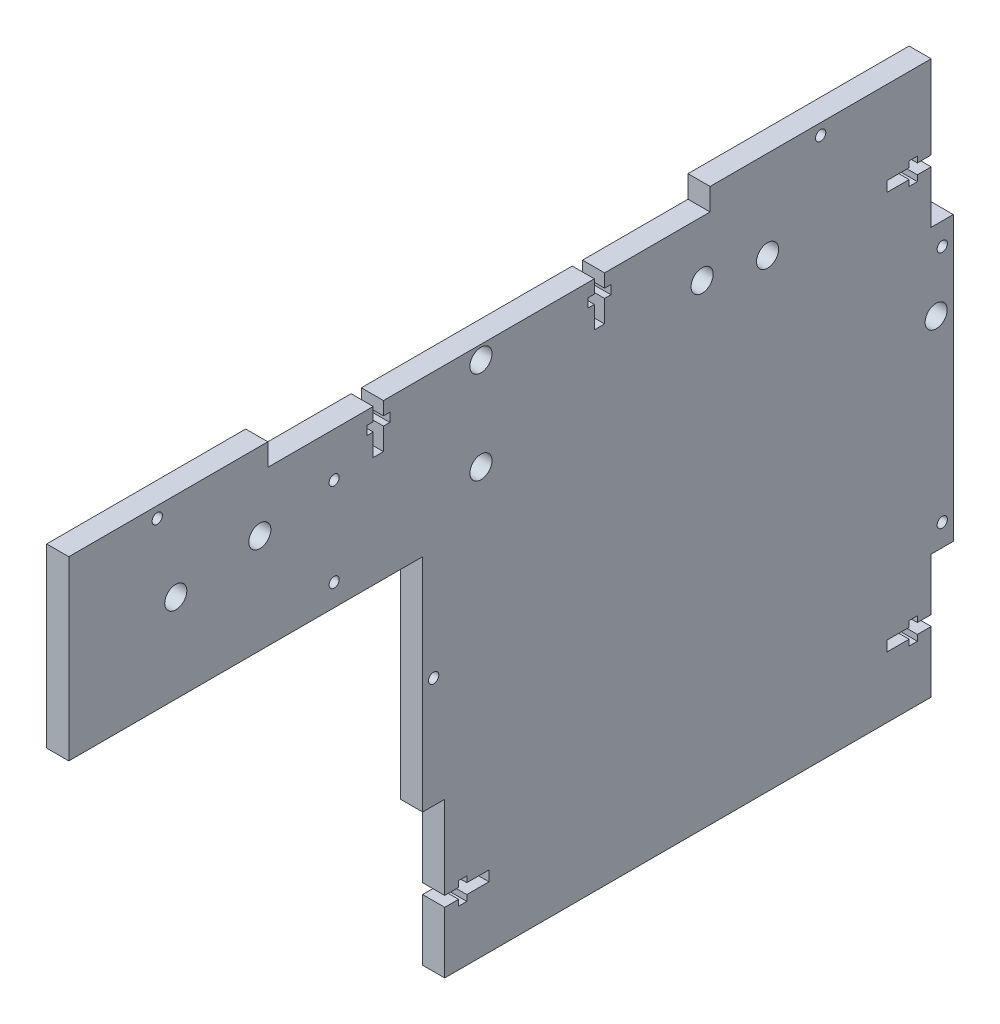
SolidWorks part; units mm, degrees
material "Acrylic (Medium-high impact)"
ref_plane "Front Plane" through (0, 0, 0) normal (0, 0, 1) x (1, 0, 0)
ref_plane "Top Plane" through (0, 0, 0) normal (0, 1, 0) x (1, 0, 0)
ref_plane "Right Plane" through (0, 0, 0) normal (1, 0, 0) x (0, 0, -1)
sketch "Sketch1" plane through (0, 0, 0) normal (1, 0, 0) x (0, 0, -1)
  line L1 (0, 0) -> (139.7, 0)
  line L2 (0, 0) -> (0, 107.95)
  line L4 (139.7, 0) -> (139.7, 158.75)
  line L7 (76.2, 158.75) -> (139.7, 158.75)
  line L8 (0, 152.4) -> (76.2, 152.4)
  line L9 (76.2, 152.4) -> (76.2, 158.75)
  line L10 (0, 152.4) -> (-50.8, 152.4)
  line L11 (-50.8, 152.4) -> (-50.8, 158.75)
  line L12 (-50.8, 158.75) -> (-107.95, 158.75)
  line L13 (-107.95, 158.75) -> (-107.95, 107.95)
  line L14 (-107.95, 107.95) -> (0, 107.95)
  dimension "D1" = 158.75
  dimension "D2" = 139.7
  dimension "D3" = 152.4
  dimension "D4" = 63.5
  dimension "D5" = 127
  dimension "D6" = 57.15
  dimension "D7" = 50.8
  dimension "D8" = 6.35
extrude "Boss-Extrude1" add sketch "Sketch1" along normal blind 6.35
sketch "Sketch2" plane through (0, 0, 0) normal (-1, 0, 0) x (0, 0, 1)
  line L0 (0, 107.95) -> (0, 0) construction
  line L1 (0, 17.5768) -> (-3.9688, 17.5768)
  line L2 (0, 17.5768) -> (0, 20.5232)
  line L3 (0, 20.5232) -> (-3.9688, 20.5232)
  line L4 (-12.7, 17.5768) -> (-12.7, 20.5232)
  line L5 (0, 17.5768) -> (6.35, 17.5768) construction
  line L6 (-6.35, 17.5768) -> (-12.7, 17.5768)
  line L7 (-3.9688, 15.875) -> (-6.35, 15.875)
  line L8 (-3.9688, 15.875) -> (-3.9688, 17.5768)
  line L9 (-3.9688, 22.225) -> (-6.35, 22.225)
  line L10 (-6.35, 15.875) -> (-6.35, 17.5768)
  line L11 (-3.9688, 20.5232) -> (-3.9688, 22.225)
  line L12 (-6.35, 20.5232) -> (-6.35, 22.225)
  line L13 (-6.35, 20.5232) -> (-12.7, 20.5232)
  line L14 (-69.85, 189.7453) -> (-69.85, -47.9109) construction
  line L16 (0, 0) -> (-139.7, 0) construction
  line L18 (-139.7, 17.5768) -> (-139.7, 20.5232)
  line L19 (-127, 17.5768) -> (-127, 20.5232)
  line L20 (-135.7313, 15.875) -> (-135.7313, 17.5768)
  line L21 (-133.35, 15.875) -> (-133.35, 17.5768)
  line L22 (-135.7313, 20.5232) -> (-135.7313, 22.225)
  line L23 (-133.35, 20.5232) -> (-133.35, 22.225)
  line L24 (-135.7313, 22.225) -> (-133.35, 22.225)
  line L25 (-135.7313, 15.875) -> (-133.35, 15.875)
  line L26 (-139.7, 17.5768) -> (-135.7313, 17.5768)
  line L27 (-139.7, 20.5232) -> (-135.7313, 20.5232)
  line L28 (-133.35, 20.5232) -> (-127, 20.5232)
  line L29 (-133.35, 17.5768) -> (-127, 17.5768)
  line L30 (-133.35, 136.525) -> (-133.35, 134.8232)
  line L31 (-135.7313, 136.525) -> (-135.7313, 134.8232)
  line L32 (-139.7, 134.8232) -> (-139.7, 131.8768)
  line L33 (-135.7313, 136.525) -> (-133.35, 136.525)
  line L34 (-139.7, 134.8232) -> (-135.7313, 134.8232)
  line L35 (-139.7, 131.8768) -> (-135.7313, 131.8768)
  line L36 (-135.7313, 131.8768) -> (-135.7313, 130.175)
  line L37 (-135.7313, 130.175) -> (-133.35, 130.175)
  line L38 (-133.35, 131.8768) -> (-133.35, 130.175)
  line L39 (-133.35, 131.8768) -> (-127, 131.8768)
  line L40 (-127, 134.8232) -> (-127, 131.8768)
  line L41 (-133.35, 134.8232) -> (-127, 134.8232)
  line L88 (-139.7, 152.4) -> (-139.7, 116.84) construction
  point P18 (-139.7, 133.35)
  point P23 (-69.85, 0)
  dimension "D1" = 2.9464
  dimension "D2" = 12.7
  dimension "D3" = 6.35
  dimension "D4" = 6.35
  dimension "D5" = 2.3813
  dimension "D6" = 6.35
  dimension "D7" = 2.3812
  dimension "D8" = 12.7
  dimension "D9" = 2.9464
  dimension "D10" = 6.35
extrude "Cut-Extrude1" cut sketch "Sketch2" against normal through all
sketch "Sketch4" plane through (0, 0, 0) normal (-1, 0, 0) x (0, 0, 1)
  line L0 (0, 107.95) -> (0, 20.5232) construction
  line L1 (0, 44.45) -> (6.35, 44.45)
  line L2 (0, 44.45) -> (0, 107.95)
  line L3 (0, 107.95) -> (6.35, 107.95)
  line L4 (6.35, 44.45) -> (6.35, 107.95)
  line L6 (-139.7, 35.56) -> (-146.05, 35.56) construction
  line L7 (107.95, 107.95) -> (0, 107.95) construction
  line L8 (-139.7, 116.84) -> (-146.05, 116.84)
  line L9 (-146.05, 35.56) -> (-146.05, 116.84)
  line L10 (-139.7, 35.56) -> (-146.05, 35.56)
  line L11 (-139.7, 35.56) -> (-139.7, 116.84)
  line L12 (-139.7, 20.5232) -> (-139.7, 131.8768) construction
  line L13 (-146.05, 35.56) -> (-146.05, 0) construction
  line L14 (-139.7, 116.84) -> (-146.05, 116.84) construction
  line L15 (0, 44.45) -> (6.35, 44.45) construction
  dimension "D1" = 6.35
extrude "Boss-Extrude3" add sketch "Sketch4" against normal up to surface (6.35 mm away)
sketch "Sketch5" plane through (0, 0, 0) normal (-1, 0, 0) x (0, 0, 1)
  line L0 (6.35, 44.45) -> (6.35, 107.95) construction
  line L1 (-74.2274, 76.2) -> (-200.83, 76.2) construction
  line L4 (-146.05, 116.84) -> (-146.05, 35.56) construction
  line L6 (-139.7, 35.56) -> (-146.05, 35.56) construction
  circle A1 centre (3.175, 76.2) radius 1.4732
  circle A2 centre (-142.875, 41.91) radius 1.4732
  circle A3 centre (-142.875, 110.49) radius 1.4732
  point P6 (6.35, 76.2)
  point P8 (-146.05, 76.2)
  point P12 (-142.875, 35.56)
  dimension "D1" = 2.9464
  dimension "D2" = 3.175
  dimension "D3" = 2.9464
  dimension "D4" = 3.175
  dimension "D5" = 6.35
extrude "Cut-Extrude2" cut sketch "Sketch5" against normal through all
sketch "Sketch6" plane through (0, 0, 0) normal (-1, 0, 0) x (0, 0, 1)
  line L1 (-42.9641, 152.4) -> (-45.9105, 152.4)
  line L2 (-42.9641, 152.4) -> (-42.9641, 148.59)
  line L3 (-42.9641, 139.7) -> (-45.9105, 139.7)
  line L4 (-45.9105, 152.4) -> (-45.9105, 148.59)
  line L5 (-41.1353, 146.05) -> (-42.9641, 146.05)
  line L6 (-41.1353, 146.05) -> (-41.1353, 148.59)
  line L7 (-41.1353, 148.59) -> (-42.9641, 148.59)
  line L8 (-47.7393, 146.05) -> (-47.7393, 148.59)
  line L10 (-76.2, 152.4) -> (50.8, 152.4) construction
  line L12 (-45.9105, 146.05) -> (-47.7393, 146.05)
  line L13 (-45.9105, 146.05) -> (-45.9105, 139.7)
  line L14 (-45.9105, 148.59) -> (-47.7393, 148.59)
  line L15 (-42.9641, 146.05) -> (-42.9641, 139.7)
  line L16 (-45.9105, 158.75) -> (-45.9105, 152.4) construction
  line L17 (-76.2, 152.4) -> (50.8, 152.4) construction
  line L18 (20.5359, 152.4) -> (17.5895, 152.4)
  line L19 (20.5359, 152.4) -> (20.5359, 148.59)
  line L20 (20.5359, 139.7) -> (17.5895, 139.7)
  line L21 (17.5895, 152.4) -> (17.5895, 148.59)
  line L22 (50.8, 158.75) -> (107.95, 158.75) construction
  line L23 (22.3647, 146.05) -> (20.5359, 146.05)
  line L24 (22.3647, 146.05) -> (22.3647, 148.59)
  line L25 (22.3647, 148.59) -> (20.5359, 148.59)
  line L26 (15.7607, 146.05) -> (15.7607, 148.59)
  line L30 (17.5895, 146.05) -> (15.7607, 146.05)
  line L31 (17.5895, 146.05) -> (17.5895, 139.7)
  line L32 (17.5895, 148.59) -> (15.7607, 148.59)
  line L33 (20.5359, 146.05) -> (20.5359, 139.7)
  line L35 (17.5895, 158.75) -> (17.5895, 152.4) construction
  circle A0 centre (-92.71, 133.35) radius 3.175
  circle A1 centre (-107.95, 155.575) radius 1.4732
  circle A2 centre (-73.914, 136.5038) radius 3.175
  circle A3 centre (82.55, 155.575) radius 1.4732
  circle A4 centre (77.2274, 133.35) radius 3.175
  circle A5 centre (53.096, 136.5038) radius 3.175
  circle A6 centre (-10.409, 121.8988) radius 3.175
  circle A7 centre (-10.409, 148.4768) radius 3.175
  circle A8 centre (-107.95, 155.575) radius 3.9624 construction
  circle A9 centre (-73.914, 136.5038) radius 3.175 construction
  circle A10 centre (-10.409, 148.4768) radius 3.175 construction
  circle A11 centre (-10.409, 121.8988) radius 3.175 construction
  circle A13 centre (-92.71, 133.35) radius 3.175 construction
  circle A14 centre (53.096, 136.5038) radius 3.175 construction
  circle A15 centre (82.55, 155.575) radius 3.9624 construction
  point P32 (-46.8249, 146.05)
  dimension "D1" = 6.35
  dimension "D2" = 6.35
  dimension "D3" = 2.9464
  dimension "D14" = 6.35
  dimension "D15" = 6.35
  dimension "D16" = 2.9464
  dimension "D27" = 6.35
  dimension "D28" = 6.35
  dimension "D9" = 2.9464
  dimension "D10" = 12.7
  dimension "D11" = 6.604
  dimension "D12" = 2.54
  dimension "D13" = 6.35
  dimension "D19" = 25.4
  dimension "D22" = 12.7
  dimension "D23" = 2.9464
  dimension "D24" = 6.604
  dimension "D25" = 2.54
  dimension "D26" = 6.35
extrude "Cut-Extrude3" cut sketch "Sketch6" against normal through all
sketch "Sketch7" plane through (6.35, 0, 0) normal (1, 0, 0) x (0, 0, -1)
  circle A0 centre (141.1194, 94.0597) radius 3.175
  dimension "D1" = 6.35
extrude "Cut-Extrude4" cut sketch "Sketch7" against normal up to next
sketch "Sketch8" plane through (0, 0, 0) normal (-1, 0, 0) x (0, 0, 1)
  line L0 (6.35, 44.45) -> (6.35, 107.95) construction
  line L1 (20.5359, 152.4) -> (50.8, 152.4) construction
  circle A0 centre (31.75, 114.3) radius 1.4605
  circle A1 centre (31.75, 139.7) radius 1.4605
  dimension "D1" = 2.921
  dimension "D2" = 2.921
  dimension "D3" = 25.4
  dimension "D4" = 25.4
  dimension "D5" = 12.7
  dimension "D6" = 25.4
extrude "Cut-Extrude5" cut sketch "Sketch8" against normal through all
